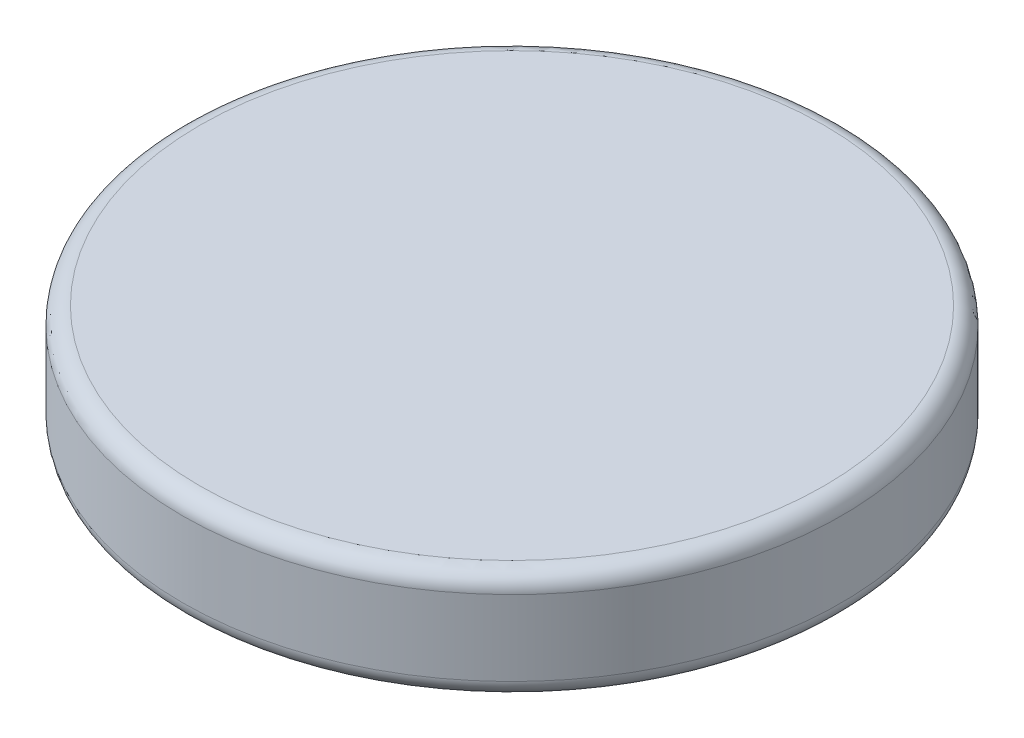
SolidWorks part; units mm, degrees
material "Stainless Steel (ferritic)"
ref_plane "Front Plane" through (0, 0, 0) normal (0, 0, 1) x (1, 0, 0)
ref_plane "Top Plane" through (0, 0, 0) normal (0, 1, 0) x (1, 0, 0)
ref_plane "Right Plane" through (0, 0, 0) normal (1, 0, 0) x (0, 0, -1)
sketch "Sketch1" plane through (0, 0, 0) normal (0, 1, 0) x (1, 0, 0)
  circle A0 centre (0, 0) radius 4.7625
  dimension "D1" = 9.525
extrude "Boss-Extrude1" add sketch "Sketch1" along normal blind 1.5875
fillet "Fillet1" radius 0.25 2 edges at (0, 0, 4.7625) (0, 1.5875, 4.7625)
